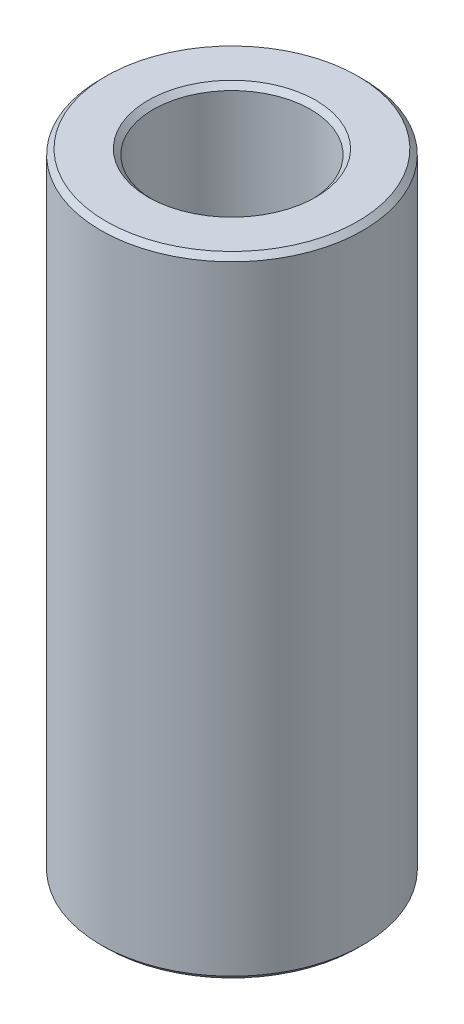
SolidWorks part; units mm, degrees
ref_plane "Front Plane" through (0, 0, 0) normal (0, 0, 1) x (1, 0, 0)
ref_plane "Top Plane" through (0, 0, 0) normal (0, 1, 0) x (1, 0, 0)
ref_plane "Right Plane" through (0, 0, 0) normal (1, 0, 0) x (0, 0, -1)
sketch "Sketch1" plane through (0, 0, 0) normal (0, 1, 0) x (1, 0, 0)
  circle A0 centre (0, 0) radius 2.5
  circle A1 centre (0, 0) radius 1.5
  dimension "D1" = 5
  dimension "D2" = 3
extrude "Boss-Extrude1" add sketch "Sketch1" along normal blind 12
chamfer "Chamfer1" distance 0.1 angle 45 4 edges at (0, 12, 1.5) (0, 12, 2.5) (0, 0, 1.5) (0, 0, 2.5)
